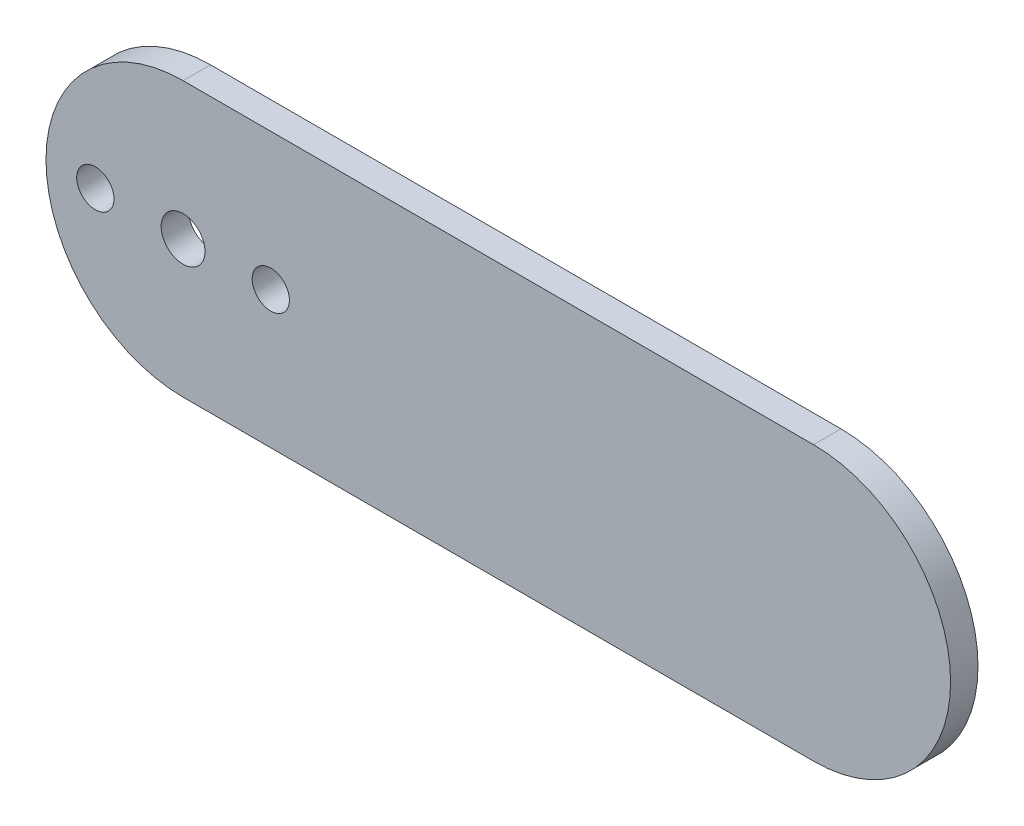
SolidWorks part; units mm, degrees
material "PPE"
ref_plane "Front Plane" through (0, 0, 0) normal (0, 0, 1) x (1, 0, 0)
ref_plane "Top Plane" through (0, 0, 0) normal (0, 1, 0) x (1, 0, 0)
ref_plane "Right Plane" through (0, 0, 0) normal (1, 0, 0) x (0, 0, -1)
sketch "Sketch2" plane through (0, 0, 0) normal (0, 0, 1) x (1, 0, 0)
  line L0 (0, 0) -> (115, 0) construction
  line L1 (0, 25) -> (115, 25)
  line L2 (0, -25) -> (115, -25)
  arc A0 (0, 25) -> (0, -25) centre (0, 0) ccw
  arc A1 (115, -25) -> (115, 25) centre (115, 0) ccw
  circle A2 centre (0, 0) radius 4
  circle A3 centre (16, 0) radius 3.4
  circle A4 centre (-16, 0) radius 3.4
  point P3 (57.5, 0)
  dimension "D3" = 8
  dimension "D4" = 6.8
  dimension "D5" = 6.8
  dimension "D6" = 16
  dimension "D7" = 16
  dimension "D1" = 115
  dimension "D2" = 50
extrude "Boss-Extrude1" add sketch "Sketch2" along normal mid plane 5
